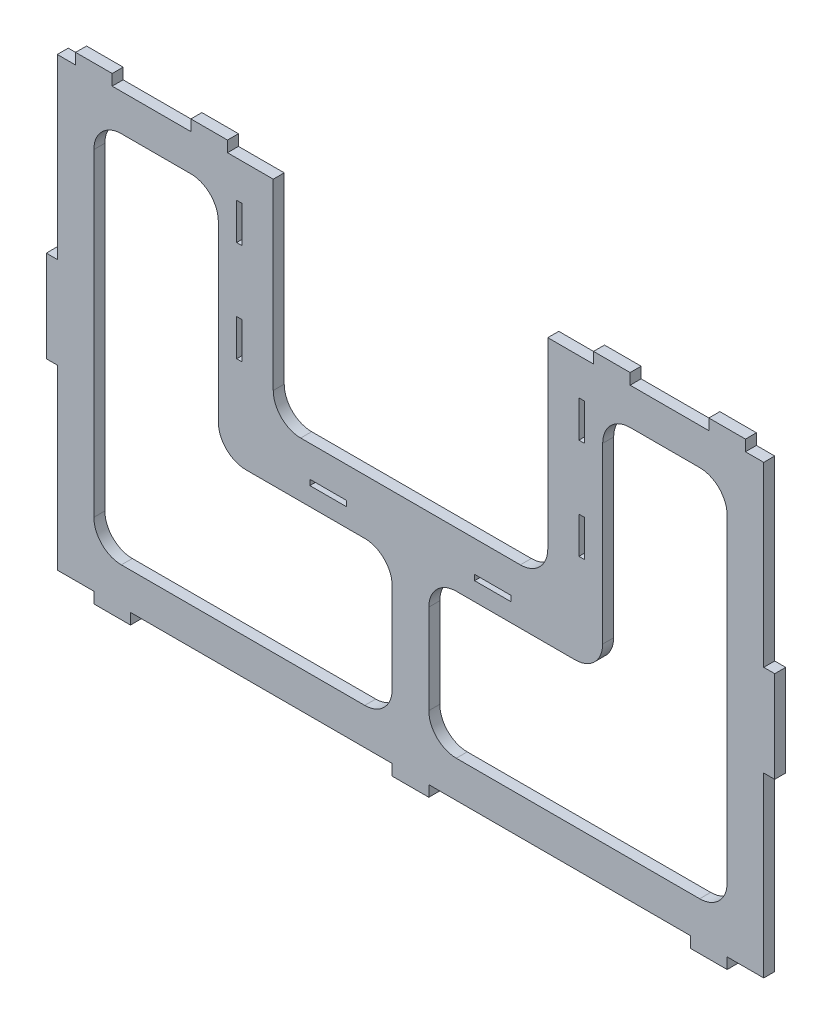
SolidWorks part; units mm, degrees
ref_plane "Спереди" through (0, 0, 0) normal (0, 0, 1) x (1, 0, 0)
ref_plane "Сверху" through (0, 0, 0) normal (0, 1, 0) x (1, 0, 0)
ref_plane "Справа" through (0, 0, 0) normal (1, 0, 0) x (0, 0, -1)
sketch "Эскиз1" plane through (0, 0, 0) normal (0, 0, 1) x (1, 0, 0)
  line L0 (118, 244) -> (118, 129)
  line L1 (0, 0) -> (386, 0) construction
  line L2 (0, 0) -> (0, 244) construction
  line L3 (0, 244) -> (118, 244) construction
  line L4 (386, 0) -> (386, 244) construction
  line L5 (118, 129) -> (268, 129)
  line L6 (268, 129) -> (268, 244)
  line L7 (20, 20) -> (20, 224)
  line L8 (20, 224) -> (88, 224)
  line L9 (88, 224) -> (88, 99)
  line L10 (88, 99) -> (183, 99)
  line L11 (298, 99) -> (298, 224)
  line L12 (298, 224) -> (366, 224)
  line L13 (366, 224) -> (366, 20)
  line L14 (366, 20) -> (203, 20)
  line L15 (268, 244) -> (386, 244) construction
  line L16 (183, 99) -> (183, 20)
  line L17 (203, 99) -> (203, 20)
  line L18 (183, 20) -> (20, 20)
  line L19 (203, 99) -> (298, 99)
  line L20 (10, 244) -> (10, 250)
  line L21 (10, 250) -> (30, 250)
  line L22 (30, 250) -> (30, 244)
  line L23 (356, 244) -> (356, 250)
  line L24 (356, 250) -> (376, 250)
  line L25 (376, 250) -> (376, 244)
  line L26 (20, 0) -> (20, -6)
  line L27 (20, -6) -> (40, -6)
  line L28 (40, -6) -> (40, 0)
  line L29 (203, 0) -> (203, -6)
  line L30 (203, -6) -> (183, -6)
  line L31 (183, -6) -> (183, 0)
  line L32 (203, 0) -> (346, 0)
  line L33 (346, 0) -> (346, -6)
  line L34 (346, -6) -> (366, -6)
  line L35 (366, -6) -> (366, 0)
  line L36 (366, 0) -> (386, 0)
  line L37 (0, 0) -> (20, 0)
  line L38 (40, 0) -> (183, 0)
  line L39 (0, 244) -> (10, 244)
  line L40 (30, 244) -> (73, 244)
  line L41 (268, 244) -> (293, 244)
  line L42 (376, 244) -> (386, 244)
  line L43 (0, 244) -> (0, 147)
  line L44 (0, 147) -> (-6, 147)
  line L45 (-6, 147) -> (-6, 97)
  line L46 (-6, 97) -> (0, 97)
  line L47 (0, 97) -> (0, 0)
  line L48 (386, 244) -> (386, 147)
  line L49 (386, 147) -> (392, 147)
  line L50 (392, 147) -> (392, 97)
  line L51 (392, 97) -> (386, 97)
  line L52 (386, 97) -> (386, 0)
  line L53 (73, 244) -> (73, 250)
  line L54 (73, 250) -> (93, 250)
  line L55 (93, 250) -> (93, 244)
  line L56 (293, 244) -> (293, 250)
  line L57 (293, 250) -> (313, 250)
  line L58 (313, 250) -> (313, 244)
  line L59 (313, 244) -> (356, 244)
  line L60 (93, 244) -> (118, 244)
  line L62 (98, 224) -> (101, 224)
  line L63 (98, 224) -> (98, 204)
  line L64 (98, 204) -> (101, 204)
  line L65 (101, 224) -> (101, 204)
  line L66 (98, 169) -> (101, 169)
  line L67 (98, 169) -> (98, 149)
  line L68 (98, 149) -> (101, 149)
  line L69 (101, 169) -> (101, 149)
  line L70 (138, 112) -> (158, 112)
  line L71 (138, 112) -> (138, 109)
  line L72 (138, 109) -> (158, 109)
  line L73 (158, 112) -> (158, 109)
  line L74 (228, 112) -> (248, 112)
  line L75 (228, 112) -> (228, 109)
  line L76 (228, 109) -> (248, 109)
  line L77 (248, 112) -> (248, 109)
  line L78 (285, 224) -> (288, 224)
  line L79 (285, 224) -> (285, 204)
  line L80 (285, 204) -> (288, 204)
  line L81 (288, 224) -> (288, 204)
  line L82 (285, 169) -> (288, 169)
  line L83 (285, 169) -> (285, 149)
  line L84 (285, 149) -> (288, 149)
  line L85 (288, 169) -> (288, 149)
  point P11 (193, 129)
  point P57 (193, -6)
  point P59 (-6, 122)
  point P60 (93, 247)
  dimension "D1" = 244
  dimension "D2" = 386
  dimension "D3" = 20
  dimension "D4" = 20
  dimension "D5" = 20
  dimension "D6" = 20
  dimension "D7" = 150
  dimension "D8" = 115
  dimension "D9" = 193
  dimension "D10" = 30
  dimension "D11" = 30
  dimension "D12" = 30
  dimension "D13" = 20
  dimension "D14" = 163
  dimension "D15" = 6
  dimension "D16" = 6
  dimension "D17" = 6
  dimension "D18" = 6
  dimension "D19" = 20
  dimension "D20" = 20
  dimension "D21" = 193
  dimension "D22" = 20
  dimension "D23" = 20
  dimension "D24" = 143
  dimension "D25" = 20
  dimension "D26" = 143
  dimension "D27" = 20
  dimension "D28" = 20
  dimension "D29" = 10
  dimension "D30" = 10
  dimension "D31" = 100
  dimension "D32" = 10
  dimension "D33" = 50
  dimension "D34" = 50
  dimension "D35" = 122
  dimension "D36" = 100
  dimension "D37" = 43
  dimension "D38" = 3
  dimension "D39" = 20
  dimension "D40" = 10
  dimension "D41" = 3
  dimension "D42" = 20
  dimension "D43" = 20
  dimension "D44" = 20
  dimension "D45" = 20
  dimension "D46" = 10
  dimension "D47" = 3
  dimension "D48" = 20
  dimension "D49" = 20
  dimension "D53" = 184
extrude "Бобышка-Вытянуть1" add sketch "Эскиз1" along normal blind 6
fillet "Скругление2" radius 15 1 edges at (366, 20, 3)
fillet "Скругление3" radius 15 1 edges at (203, 99, 3)
fillet "Скругление4" radius 15 1 edges at (203, 20, 3)
fillet "Скругление5" radius 15 1 edges at (298, 99, 3)
fillet "Скругление6" radius 15 1 edges at (298, 224, 3)
fillet "Скругление7" radius 15 1 edges at (366, 224, 3)
fillet "Скругление8" radius 15 1 edges at (183, 99, 3)
fillet "Скругление9" radius 15 1 edges at (20, 224, 3)
fillet "Скругление10" radius 15 1 edges at (88, 99, 3)
fillet "Скругление11" radius 15 1 edges at (88, 224, 3)
fillet "Скругление12" radius 15 1 edges at (183, 20, 3)
fillet "Скругление13" radius 15 1 edges at (20, 20, 3)
fillet "Скругление14" radius 15 1 edges at (268, 129, 3)
fillet "Скругление15" radius 15 1 edges at (118, 129, 3)
